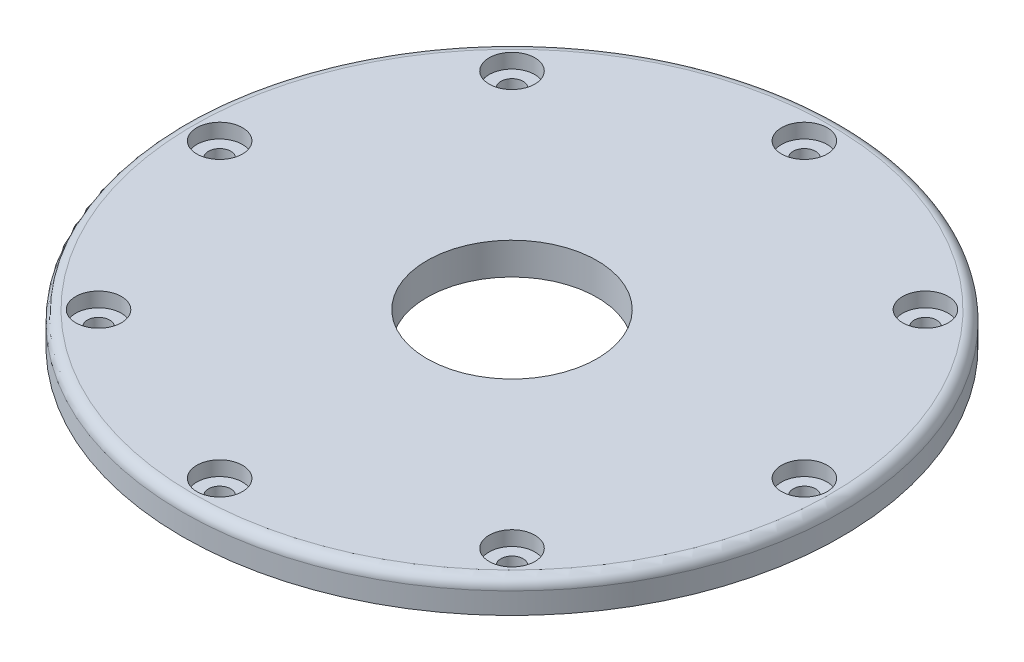
SolidWorks part; units mm, degrees
ref_plane "Front Plane" through (0, 0, 0) normal (0, 0, 1) x (1, 0, 0)
ref_plane "Top Plane" through (0, 0, 0) normal (0, 1, 0) x (1, 0, 0)
ref_plane "Right Plane" through (0, 0, 0) normal (1, 0, 0) x (0, 0, -1)
sketch "Sketch1" plane through (0, 0, 0) normal (0, 1, 0) x (1, 0, 0)
  circle A0 centre (0, 0) radius 155
  dimension "D1" = 310
extrude "Boss-Extrude1" add sketch "Sketch1" along normal blind 15
sketch "Sketch2" plane through (0, 15, 0) normal (0, 1, 0) x (1, 0, 0)
  line L0 (0, 0) -> (0, 137.5) construction
  circle A0 centre (0, 0) radius 137.5
  circle A1 centre (0, 0) radius 40
  dimension "D1" = 275
  dimension "D2" = 80
hole_wizard "CBORE for M10 Hex Head Bolt1" positions "3DSketch1" profile "Sketch4" counterbore size "M10" standard "ANSI Metric" end condition through all
sketch3d "3DSketch1"
  point P0 (0, 15, -137.5)
sketch "Sketch4" plane through (0, 15, -137.5) normal (1, 0, 0) x (0, 0, 1)
  line L0 (0, 0) -> (0, 15)
  line L1 (0, 15) -> (5.25, 15)
  line L3 (5.25, 15) -> (5.25, 6.85)
  line L4 (5.25, 6.85) -> (10.74, 6.85)
  line L5 (10.74, 6.85) -> (10.74, 0)
  line L7 (10.74, 0) -> (0, 0)
  line L11 (0, -6.35) -> (0, 107.95) construction
  dimension "Thru Hole Dia." = 10.5
  dimension "Thru Hole Depth" = 15
  dimension "C'Bore Dia." = 21.48
  dimension "C'Bore Depth" = 6.85
pattern_circular "CirPattern1" count 8 over 360 about axis through (0, 0, 0) along (0, 1, 0) of "CBORE for M10 Hex Head Bolt1"
extrude "Cut-Extrude1" cut sketch "Sketch2" against normal blind 15
fillet "Fillet1" radius 5 1 edges at (0, 15, 155)
